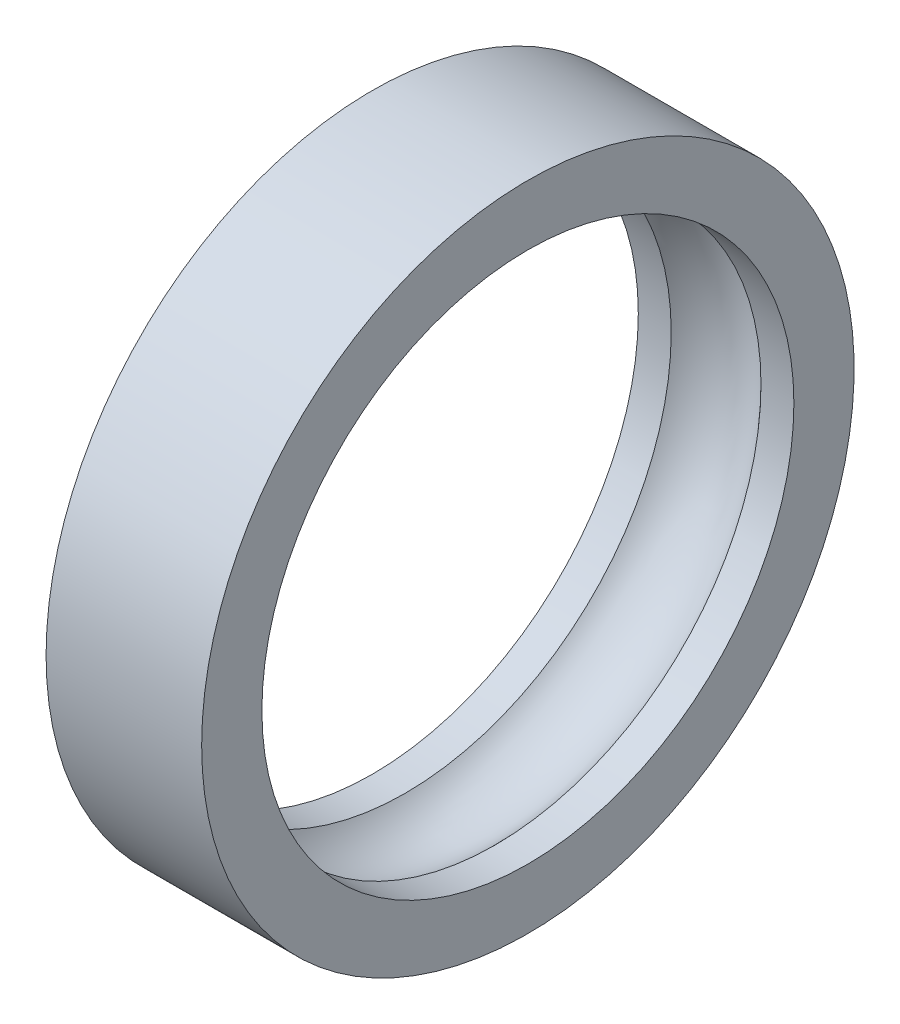
SolidWorks part; units mm, degrees
ref_plane "Front Plane" through (0, 0, 0) normal (0, 0, 1) x (1, 0, 0)
ref_plane "Top Plane" through (0, 0, 0) normal (0, 1, 0) x (1, 0, 0)
ref_plane "Right Plane" through (0, 0, 0) normal (1, 0, 0) x (0, 0, -1)
sketch "Sketch1" plane through (0, 0, 0) normal (0, 0, 1) x (1, 0, 0)
  line L0 (-15.5, 0) -> (33.0253, 0) construction
  line L1 (-8.9443, 53) -> (-15.5, 53)
  line L2 (15.5, 53) -> (8.9443, 53)
  line L3 (15.5, 53) -> (15.5, 65)
  line L4 (15.5, 65) -> (-15.5, 65)
  line L5 (-15.5, 53) -> (-15.5, 65)
  line L6 (15.5, 53) -> (-15.5, 65) construction
  line L7 (15.5, 65) -> (-15.5, 53) construction
  line L8 (0, 0) -> (0, 6.6185) construction
  line L9 (0, 53) -> (0, 0) construction
  arc A0 (-8.9443, 53) -> (8.9443, 53) centre (0, 45) cw
  point P3 (0, 59)
  dimension "D5" = 12
  dimension "D1" = 31
  dimension "D2" = 53
  dimension "D3" = 65
  dimension "D4" = 8
revolve "Revolve1" add sketch "Sketch1" angle 360 about L0
